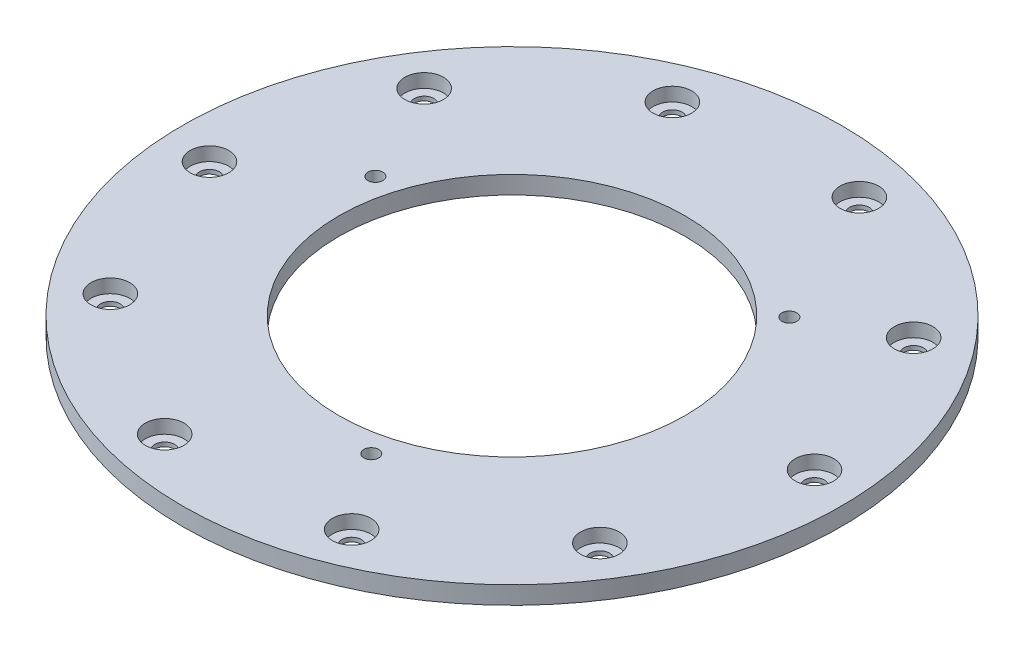
SolidWorks part; units mm, degrees
ref_plane "Alzado" through (0, 0, 0) normal (0, 0, 1) x (1, 0, 0)
ref_plane "Planta" through (0, 0, 0) normal (0, 1, 0) x (1, 0, 0)
ref_plane "Vista lateral" through (0, 0, 0) normal (1, 0, 0) x (0, 0, -1)
sketch "Croquis1" plane through (0, 0, 0) normal (0, 1, 0) x (1, 0, 0)
  circle A0 centre (0, 0) radius 110.9
  dimension "D1" = 221.8
extrude "Saliente-Extruir1" add sketch "Croquis1" along normal blind 6
sketch "Croquis2" plane through (0, 6, 0) normal (0, 1, 0) x (1, 0, 0)
  circle A0 centre (0, 0) radius 58.25
  dimension "D1" = 116.5
extrude "Cortar-Extruir1" cut sketch "Croquis2" against normal blind 6
hole_wizard "Refrentado para tornillo con cabeza troncocónica de M61" positions "Croquis4" profile "Croquis3" counterbore size "M6" standard "Ansi Metric" end condition through all
sketch "Croquis4" plane through (0, 6, 0) normal (0, 1, 0) x (1, 0, 0)
  line L0 (-35.3047, 89.2725) -> (0, 0) construction
  point P0 (-35.3047, 89.2725)
  point P12 (23.911, 92.9745)
  point P13 (73.9934, 61.1635)
  point P14 (95.8129, 5.99)
  point P15 (81.0352, -51.4714)
  point P16 (35.3047, -89.2725)
  point P17 (-23.911, -92.9745)
  point P18 (-73.9934, -61.1635)
  point P19 (-95.8129, -5.99)
  point P20 (-81.0352, 51.4714)
  point P21 (0, 0)
  dimension "D1" = 96
  dimension "D2" = 10
sketch "Croquis3" plane through (-35.3047, 6, -89.2725) normal (1, 0, 0) x (0, 0, 1)
  line L0 (0, 0) -> (0, 6)
  line L1 (0, 6) -> (3.3, 6)
  line L3 (3.3, 6) -> (3.3, 4.6)
  line L4 (3.3, 4.6) -> (6.5, 4.6)
  line L5 (6.5, 4.6) -> (6.5, 0)
  line L7 (6.5, 0) -> (0, 0)
  line L11 (0, -6.35) -> (0, 107.95) construction
  dimension "Diámetro de taladro hasta el siguiente" = 6.6
  dimension "Profundidad de taladro hasta el siguiente" = 6
  dimension "Diámetro de refrentado" = 13
  dimension "Profundidad de refrentado" = 4.6
hole_wizard "Taladro roscado M6x1.01" positions "Croquis6" profile "Croquis5" tap size "M6x1.0" standard "Ansi Metric" end condition through all
sketch "Croquis6" plane through (0, 6, 0) normal (0, 1, 0) x (1, 0, 0)
  line L0 (-63.6023, 17.6281) -> (0, 0) construction
  point P0 (-63.6023, 17.6281)
  point P14 (47.0675, 46.2671)
  point P15 (16.5347, -63.8952)
  point P16 (0, 0)
  dimension "D1" = 66
  dimension "D2" = 3
sketch "Croquis5" plane through (-63.6023, 6, -17.6281) normal (1, 0, 0) x (0, 0, 1)
  line L0 (0, 0) -> (0, 6)
  line L1 (0, 6) -> (2.5, 6)
  line L2 (2.5, 6) -> (2.5, 0)
  line L5 (2.5, 0) -> (0, 0)
  line L11 (0, -6.35) -> (0, 107.95) construction
  dimension "Diámetro mayor de rosca" = 5
  dimension "Profundidad de perforador para roscar hasta el siguiente" = 6
